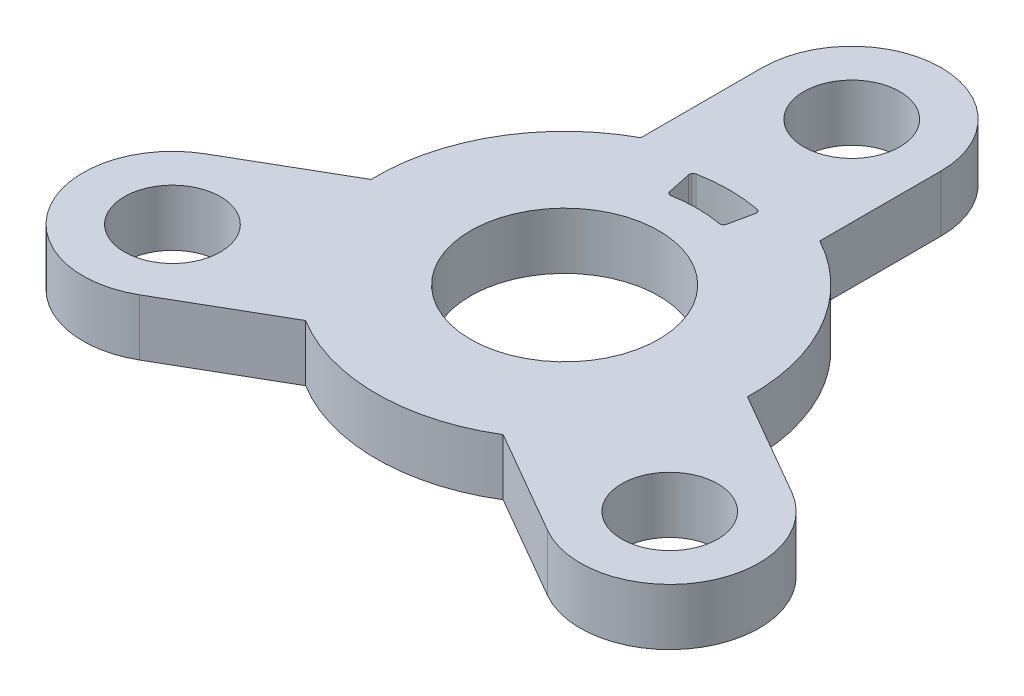
SolidWorks part; units mm, degrees
ref_plane "Front Plane" through (0, 0, 0) normal (0, 0, 1) x (1, 0, 0)
ref_plane "Top Plane" through (0, 0, 0) normal (0, 1, 0) x (1, 0, 0)
ref_plane "Right Plane" through (0, 0, 0) normal (1, 0, 0) x (0, 0, -1)
sketch "Sketch1" plane through (0, 0, 0) normal (0, 1, 0) x (1, 0, 0)
  circle A0 centre (0, 0) radius 5
  circle A2 centre (0, 0) radius 10
  dimension "D1" = 10
  dimension "D2" = 20
extrude "Boss-Extrude1" add sketch "Sketch1" along normal blind 3
sketch "Sketch2" plane through (0, 3, 0) normal (0, 1, 0) x (1, 0, 0)
  line L0 (-4.75, 15.25) -> (-4.75, 8.7999)
  line L1 (4.75, 15.25) -> (4.75, 8.7999)
  circle A0 centre (0, 15.25) radius 2.55
  arc A1 (4.75, 15.25) -> (-4.75, 15.25) centre (0, 15.25) ccw
  circle A2 centre (0, 0) radius 10 construction
  arc A3 (-4.75, 8.7999) -> (4.75, 8.7999) centre (0, 0) cw
  dimension "D1" = 5.1
  dimension "D2" = 9.5
  dimension "D3" = 15.25
extrude "Boss-Extrude2" add sketch "Sketch2" against normal up to surface (3 mm away) up to face at (0, 0, 10)
pattern_circular "CirPattern1" count 3 over 360 about axis through (0, 0, 0) along (0, 1, 0) of "Boss-Extrude2"
sketch "Sketch3" plane through (0, 3, 0) normal (0, 1, 0) x (1, 0, 0)
  line L0 (-1.8192, 8.5588) -> (-1.4658, 6.8959)
  line L1 (1.8192, 8.5588) -> (1.4658, 6.8959)
  line L2 (-1.8192, 8.5588) -> (0, 0) construction
  line L3 (0, 0) -> (1.8192, 8.5588) construction
  line L4 (0, 0) -> (0, 8.75) construction
  circle A0 centre (0, 0) radius 8.75 construction
  circle A1 centre (0, 0) radius 7.05 construction
  arc A2 (-1.4658, 6.8959) -> (1.4658, 6.8959) centre (0, 0) cw
  arc A3 (-1.8192, 8.5588) -> (1.8192, 8.5588) centre (0, 0) cw
  dimension "D1" = 14.1
  dimension "D2" = 17.5
  dimension "D3" = 24
  dimension "D4" = 12
extrude "Cut-Extrude1" cut sketch "Sketch3" against normal through all
fillet "Fillet1" radius 0.2 4 edges at (-1.4658, 1.5, -6.8959) (1.4658, 1.5, -6.8959) (1.8192, 1.5, -8.5588) (-1.8192, 1.5, -8.5588)
